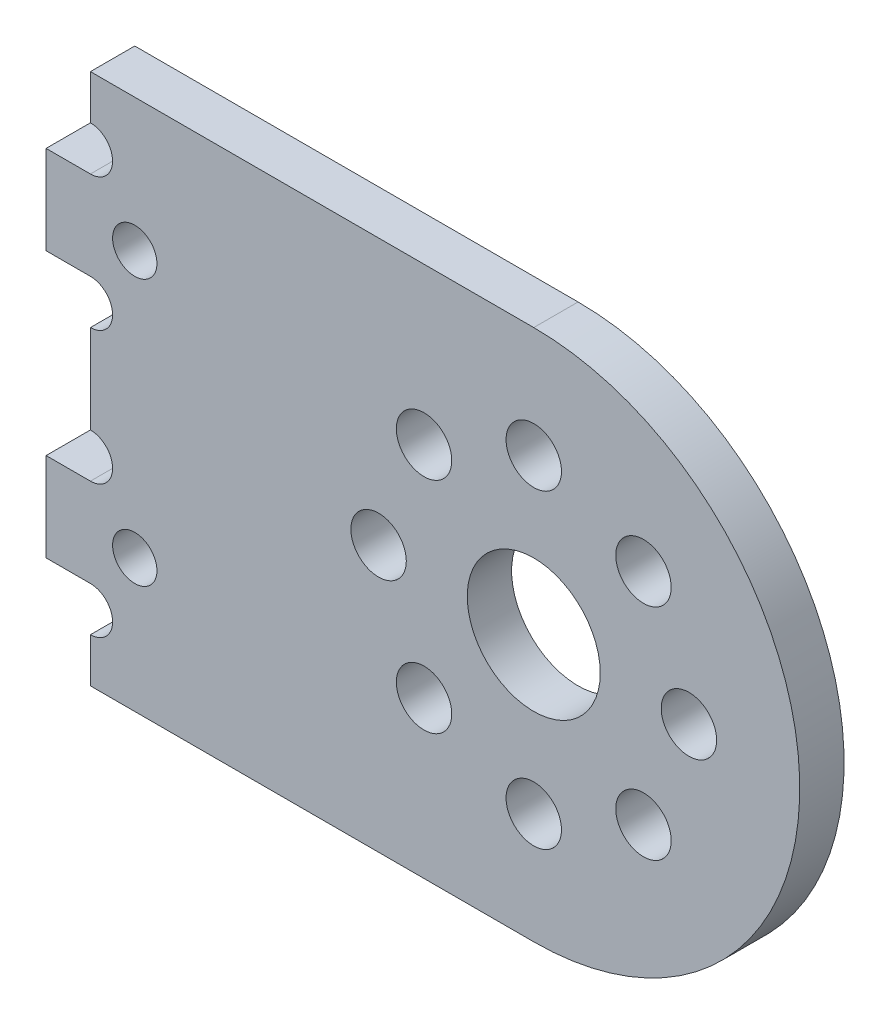
SolidWorks part; units mm, degrees
material "自訂玻璃纖維"
ref_plane "前基準面" through (0, 0, 0) normal (0, 0, 1) x (1, 0, 0)
ref_plane "上基準面" through (0, 0, 0) normal (0, 1, 0) x (1, 0, 0)
ref_plane "右基準面" through (0, 0, 0) normal (1, 0, 0) x (0, 0, -1)
sketch "草圖8" plane through (0, 0, 0) normal (0, 0, 1) x (1, 0, 0)
  line L0 (-23.4048, 11.8614) -> (-23.4048, 9.8614)
  line L1 (-23.4048, 11.8614) -> (-3.4048, 11.8614)
  line L2 (-3.4048, -12.1386) -> (-23.4048, -12.1386)
  line L3 (-23.4048, 1.8614) -> (-23.4048, -2.1386)
  line L4 (-23.4048, 7.8614) -> (-25.4048, 7.8614)
  line L5 (-25.4048, -4.1386) -> (-25.4048, -8.1386)
  line L6 (-23.4048, 3.8614) -> (-25.4048, 3.8614)
  line L7 (-25.4048, 7.8614) -> (-25.4048, 3.8614)
  line L8 (-23.4048, -4.1386) -> (-25.4048, -4.1386)
  line L9 (-23.4048, -8.1386) -> (-25.4048, -8.1386)
  line L10 (-23.4048, -10.1386) -> (-23.4048, -12.1386)
  arc A0 (-3.4048, 11.8614) -> (-3.4048, -12.1386) centre (-3.4048, -0.1386) cw
  circle A1 centre (-3.4048, 6.8614) radius 1.25
  circle A2 centre (1.545, 4.8111) radius 1.25
  circle A3 centre (-3.4048, -0.1386) radius 3
  circle A4 centre (3.5952, -0.1386) radius 1.25
  circle A5 centre (1.545, -5.0884) radius 1.25
  circle A6 centre (-3.4048, -7.1386) radius 1.25
  circle A7 centre (-8.3545, -5.0884) radius 1.25
  circle A8 centre (-10.4048, -0.1386) radius 1.25
  circle A9 centre (-8.3545, 4.8111) radius 1.25
  arc A10 (-23.4048, 7.8614) -> (-23.4048, 9.8614) centre (-23.4048, 8.8614) ccw
  circle A11 centre (-21.4048, 5.8614) radius 1
  circle A12 centre (-21.4048, -6.1386) radius 1
  arc A13 (-23.4048, 3.8614) -> (-23.4048, 1.8614) centre (-23.4048, 2.8614) cw
  arc A14 (-23.4048, -8.1386) -> (-23.4048, -10.1386) centre (-23.4048, -9.1386) cw
  arc A15 (-23.4048, -4.1386) -> (-23.4048, -2.1386) centre (-23.4048, -3.1386) ccw
  point P28 (-3.4048, -0.1386)
  point P30 (-4.4056, -0.9391)
  point P40 (-4.4056, -0.1386)
  dimension "D1" = 2.5
  dimension "D2" = 7
  dimension "D3" = 6
  dimension "D5" = 4
  dimension "D7" = 20
  dimension "D8" = 2
  dimension "D13" = 12
  dimension "D14" = 4
  dimension "D11" = 24
  dimension "D15" = 2
  dimension "D4" = 8
extrude "填料-伸長1" add sketch "草圖8" along normal blind 2
